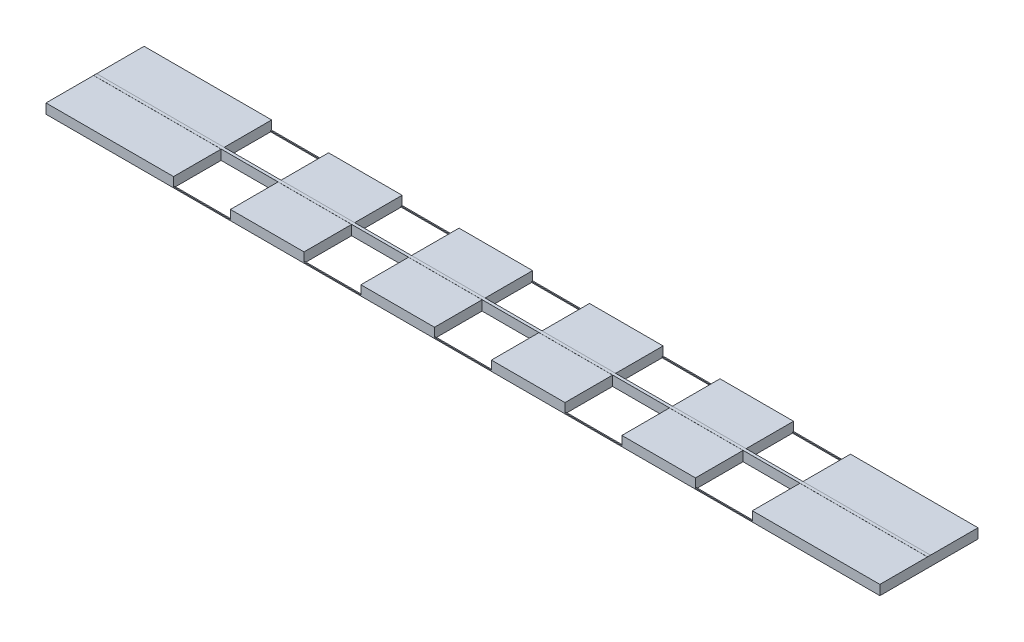
SolidWorks part; units mm, degrees
ref_plane "Front Plane" through (0, 0, 0) normal (0, 0, 1) x (1, 0, 0)
ref_plane "Top Plane" through (0, 0, 0) normal (0, 1, 0) x (1, 0, 0)
ref_plane "Right Plane" through (0, 0, 0) normal (1, 0, 0) x (0, 0, -1)
sketch "Sketch1" plane through (0, 0, 0) normal (0, 1, 0) x (1, 0, 0)
  line L1 (-4250, -500) -> (4250, -500)
  line L2 (-4250, -500) -> (-4250, 500)
  line L3 (-4250, 500) -> (4250, 500)
  line L4 (4250, -500) -> (4250, 500)
  line L5 (-4250, -500) -> (4250, 500) construction
  line L6 (-4250, 500) -> (4250, -500) construction
  point P0 (0, 0)
  dimension "D1" = 8500
  dimension "D2" = 1000
extrude "Boss-Extrude1" add sketch "Sketch1" along normal blind 100
sketch "Sketch2" plane through (0, 100, 0) normal (0, 1, 0) x (1, 0, 0)
  line L0 (4250, -500) -> (4250, 500) construction
  line L1 (-4250, -15) -> (4250, -15)
  line L2 (-4250, -15) -> (-4250, 15)
  line L3 (-4250, 15) -> (4250, 15)
  line L4 (4250, -15) -> (4250, 15)
  line L5 (-4250, -15) -> (4250, 15) construction
  line L6 (-4250, 15) -> (4250, -15) construction
  point P0 (0, 0)
  dimension "D1" = 30
extrude "Boss-Extrude2" add sketch "Sketch2" along normal blind 1 separate body
sketch "Sketch3" plane through (0, 100, 0) normal (0, 1, 0) x (1, 0, 0)
  line L0 (-4250, 500) -> (-2950, 500) construction
  line L1 (4250, 500) -> (-4250, 500) construction
  line L2 (-2950, 500) -> (-2950, 490) construction
  line L3 (4250, 15) -> (-4250, 15) construction
  line L4 (-2950, 490) -> (-2370, 490)
  line L5 (-2950, 490) -> (-2950, 15)
  line L6 (-2950, 15) -> (-2370, 15)
  line L7 (-2370, 490) -> (-2370, 15)
  line L8 (-1620, 490) -> (-1620, 15)
  line L9 (-1620, 490) -> (-1040, 490)
  line L10 (-1040, 490) -> (-1040, 15)
  line L11 (-1620, 15) -> (-1040, 15)
  line L12 (-290, 490) -> (-290, 15)
  line L13 (-290, 490) -> (290, 490)
  line L14 (290, 490) -> (290, 15)
  line L15 (-290, 15) -> (290, 15)
  line L16 (1040, 490) -> (1040, 15)
  line L17 (1040, 490) -> (1620, 490)
  line L18 (1620, 490) -> (1620, 15)
  line L19 (1040, 15) -> (1620, 15)
  line L20 (2370, 490) -> (2370, 15)
  line L21 (2370, 490) -> (2950, 490)
  line L22 (2950, 490) -> (2950, 15)
  line L23 (2370, 15) -> (2950, 15)
  line L24 (-1620, -15) -> (-1620, -490)
  line L25 (-1620, -15) -> (-1040, -15)
  line L26 (-1040, -15) -> (-1040, -490)
  line L27 (-1620, -490) -> (-1040, -490)
  line L28 (-290, -15) -> (-290, -490)
  line L29 (-290, -15) -> (290, -15)
  line L30 (290, -15) -> (290, -490)
  line L31 (-290, -490) -> (290, -490)
  line L32 (1040, -15) -> (1040, -490)
  line L33 (1040, -15) -> (1620, -15)
  line L34 (1620, -15) -> (1620, -490)
  line L35 (1040, -490) -> (1620, -490)
  line L36 (2370, -15) -> (2370, -490)
  line L37 (2370, -15) -> (2950, -15)
  line L38 (2950, -15) -> (2950, -490)
  line L39 (2370, -490) -> (2950, -490)
  line L40 (-2950, -15) -> (-2950, -490)
  line L41 (-2950, -15) -> (-2370, -15)
  line L42 (-2370, -15) -> (-2370, -490)
  line L43 (-2950, -490) -> (-2370, -490)
  line L44 (-4250, 500) -> (-4250, -500) construction
  dimension "D1" = 1300
  dimension "D2" = 10
  dimension "D3" = 580
  dimension "D6" = 750
  dimension "D7" = 30
  dimension "D8" = 1300
  dimension "D4" = 5
  dimension "D5" = 2
extrude "Cut-Extrude2" cut sketch "Sketch3" against normal through all
sketch "Sketch4" plane through (0, 100, 0) normal (0, 1, 0) x (1, 0, 0)
  line L0 (4250, 500) -> (-4250, 500) construction
  line L1 (-2950, 500) -> (-2370, 500)
  line L2 (-2950, 500) -> (-2950, 490)
  line L3 (-2950, 490) -> (-2370, 490)
  line L4 (-2370, 500) -> (-2370, 490)
  line L5 (-1620, 490) -> (-1040, 490)
  line L6 (-1620, 500) -> (-1040, 500)
  line L7 (-1040, 500) -> (-1040, 490)
  line L8 (-1620, 500) -> (-1620, 490)
  line L9 (-290, 490) -> (290, 490)
  line L10 (-290, 500) -> (290, 500)
  line L11 (290, 500) -> (290, 490)
  line L12 (-290, 500) -> (-290, 490)
  line L13 (1040, 490) -> (1620, 490)
  line L14 (1040, 500) -> (1620, 500)
  line L15 (1620, 500) -> (1620, 490)
  line L16 (1040, 500) -> (1040, 490)
  line L17 (2370, 490) -> (2950, 490)
  line L18 (2370, 500) -> (2950, 500)
  line L19 (2950, 500) -> (2950, 490)
  line L20 (2370, 500) -> (2370, 490)
  line L21 (-1620, -500) -> (-1040, -500)
  line L22 (-1620, -490) -> (-1040, -490)
  line L23 (-1040, -490) -> (-1040, -500)
  line L24 (-1620, -490) -> (-1620, -500)
  line L25 (-290, -500) -> (290, -500)
  line L26 (-290, -490) -> (290, -490)
  line L27 (290, -490) -> (290, -500)
  line L28 (-290, -490) -> (-290, -500)
  line L29 (1040, -500) -> (1620, -500)
  line L30 (1040, -490) -> (1620, -490)
  line L31 (1620, -490) -> (1620, -500)
  line L32 (1040, -490) -> (1040, -500)
  line L33 (2370, -500) -> (2950, -500)
  line L34 (2370, -490) -> (2950, -490)
  line L35 (2950, -490) -> (2950, -500)
  line L36 (2370, -490) -> (2370, -500)
  line L37 (-2950, -500) -> (-2370, -500)
  line L38 (-2950, -490) -> (-2370, -490)
  line L39 (-2370, -490) -> (-2370, -500)
  line L40 (-2950, -490) -> (-2950, -500)
  line L42 (-4250, 500) -> (-4250, -500) construction
  dimension "D1" = 580
  dimension "D4" = 980
  dimension "D5" = 750
  dimension "D6" = 1300
  dimension "D2" = 5
  dimension "D3" = 2
extrude "Cut-Extrude3" cut sketch "Sketch4" against normal blind 90
